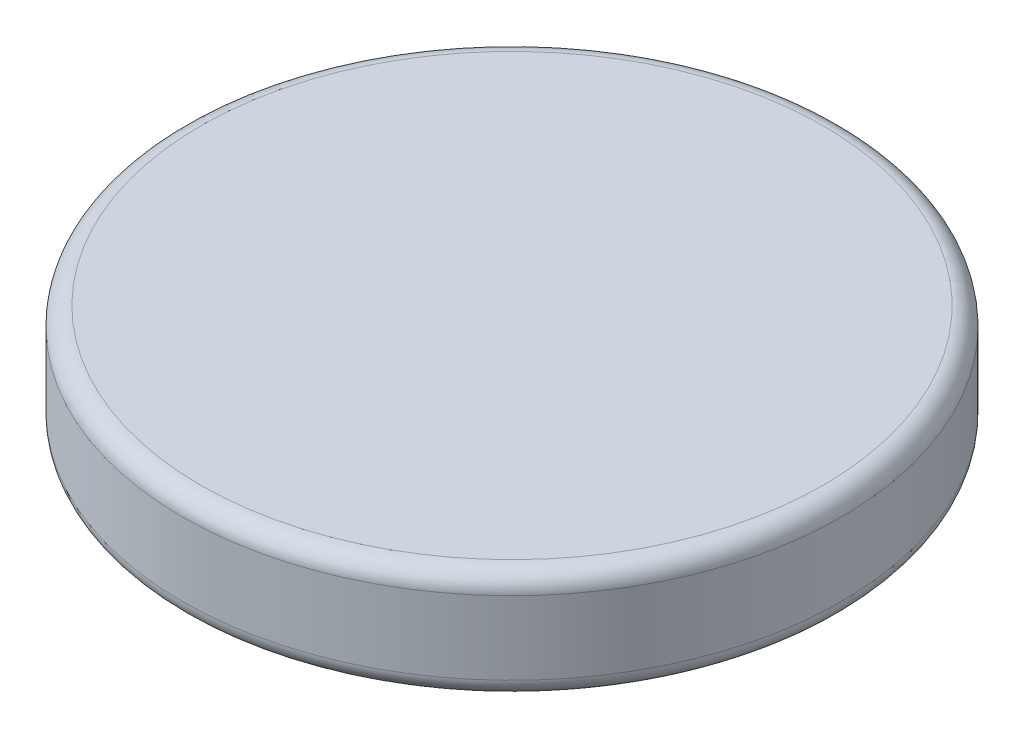
SolidWorks part; units mm, degrees
material "Duranickel(R) 301"
ref_plane "Front Plane" through (0, 0, 0) normal (0, 0, 1) x (1, 0, 0)
ref_plane "Top Plane" through (0, 0, 0) normal (0, 1, 0) x (1, 0, 0)
ref_plane "Right Plane" through (0, 0, 0) normal (1, 0, 0) x (0, 0, -1)
sketch "Sketch1" plane through (0, 0, 0) normal (0, 1, 0) x (1, 0, 0)
  circle A0 centre (0, 0) radius 9
  dimension "D1" = 18
extrude "Boss-Extrude1" add sketch "Sketch1" along normal blind 3
fillet "Fillet1" radius 0.5 2 edges at (0, 0, 9) (0, 3, 9)
